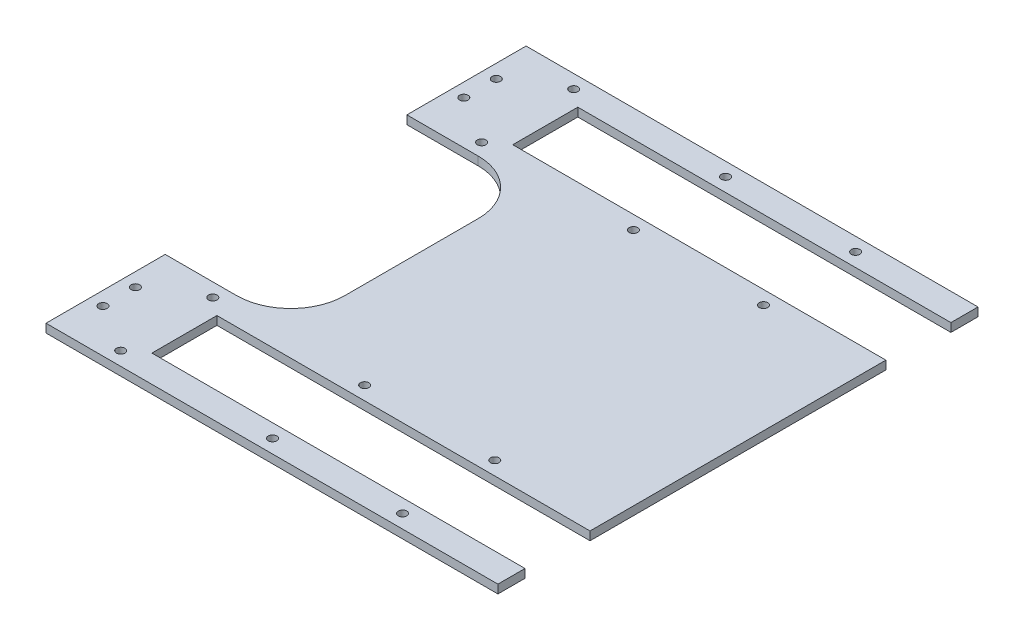
SolidWorks part; units mm, degrees
ref_plane "Front Plane" through (0, 0, 0) normal (0, 0, 1) x (1, 0, 0)
ref_plane "Top Plane" through (0, 0, 0) normal (0, 1, 0) x (1, 0, 0)
ref_plane "Right Plane" through (0, 0, 0) normal (1, 0, 0) x (0, 0, -1)
sketch "Sketch1" plane through (0, 0, 0) normal (0, 1, 0) x (1, 0, 0)
  line L0 (-55.952, 28.5339) -> (-55.9511, 28.5339)
  line L1 (-55.9511, 28.5339) -> (-55.9511, 28.321)
  line L2 (-55.9511, 28.321) -> (-21.4553, 28.321)
  line L3 (-21.4553, 28.321) -> (-21.4553, -28.321)
  line L4 (-21.4553, -28.321) -> (-55.952, -28.321)
  line L5 (-55.952, -28.321) -> (-55.952, -63.881)
  line L6 (-55.952, -63.881) -> (55.046, -63.881)
  line L7 (55.046, -63.881) -> (55.046, -57.531)
  line L8 (55.046, -57.531) -> (32.4585, -57.531)
  line L10 (32.4585, -34.671) -> (55.046, -34.671)
  line L11 (55.046, -34.671) -> (55.046, 34.671)
  line L12 (55.046, 34.671) -> (32.4585, 34.671)
  line L14 (32.4585, 57.531) -> (55.046, 57.531)
  line L15 (55.046, 57.531) -> (55.046, 63.881)
  line L16 (55.046, 63.881) -> (-55.952, 63.881)
  line L17 (-55.952, 63.881) -> (-55.952, 28.5339)
  line L18 (-21.4553, 0) -> (55.046, 0) construction
  line L19 (-55.952, -46.101) -> (-28.5899, -46.101) construction
  line L20 (32.4585, -34.671) -> (-28.5899, -34.671)
  line L21 (-28.5899, -34.671) -> (-28.5899, -46.101)
  line L22 (-28.5899, -46.101) -> (-28.5899, -57.531)
  line L23 (-28.5899, -57.531) -> (32.4585, -57.531)
  line L24 (-28.5899, 57.531) -> (32.4585, 57.531)
  line L25 (-28.5899, 46.101) -> (-28.5899, 57.531)
  line L26 (-28.5899, 34.671) -> (-28.5899, 46.101)
  line L27 (32.4585, 34.671) -> (-28.5899, 34.671)
  dimension "D1" = 28.321
  dimension "D2" = 27.3621
extrude "Boss-Extrude1" add sketch "Sketch1" along normal blind 2
fillet "Fillet1" radius 12.7 2 edges at (-21.4553, 1, 28.321) (-21.4553, 1, -28.321)
sketch "Sketch2" plane through (0, 2, 0) normal (0, 1, 0) x (1, 0, 0)
  line L36 (0, 0) -> (55.046, 0) construction
  line L37 (55.046, -34.671) -> (55.046, 34.671) construction
  circle A0 centre (51.871, 0) radius 1
  circle A1 centre (51.871, 14.1605) radius 1
  circle A2 centre (-18.2803, 0) radius 1
  circle A3 centre (-18.2803, -14.1605) radius 1
  circle A4 centre (-18.2803, 14.1605) radius 1
  circle A5 centre (-36.539, 31.496) radius 1
  circle A6 centre (-0.9481, 31.496) radius 1
  circle A7 centre (29.5319, 31.4883) radius 1
  circle A8 centre (-52.777, 45.1485) radius 1
  circle A9 centre (-52.777, 53.4035) radius 1
  circle A10 centre (-36.539, 60.706) radius 1
  circle A11 centre (-0.9481, 60.706) radius 1
  circle A12 centre (29.5319, 60.7137) radius 1
  circle A13 centre (29.5319, -60.7137) radius 1
  circle A14 centre (-0.9481, -60.706) radius 1
  circle A15 centre (-36.539, -60.706) radius 1
  circle A16 centre (-52.777, -53.4035) radius 1
  circle A17 centre (-52.777, -45.1485) radius 1
  circle A18 centre (29.5319, -31.4883) radius 1
  circle A19 centre (-0.9481, -31.496) radius 1
  circle A20 centre (-36.539, -31.496) radius 1
  circle A21 centre (51.871, -14.1605) radius 1
  dimension "D1" = 2
extrude "Cut-Extrude1" cut sketch "Sketch2" against normal through all both and the other way through all
sketch "Sketch3" plane through (0, 2, 0) normal (0, 1, 0) x (1, 0, 0)
  line L0 (-28.5899, -57.531) -> (-32.3999, -57.531)
  line L1 (-32.3999, -57.531) -> (-32.3999, -34.671)
  line L2 (-32.3999, -34.671) -> (-28.5899, -34.671)
  line L3 (-28.5899, -34.671) -> (-28.5899, -57.531)
  line L4 (-21.4553, 0) -> (55.046, 0) construction
  line L5 (-21.4553, 15.621) -> (-21.4553, -15.621) construction
  line L6 (55.046, -34.671) -> (55.046, 34.671) construction
  line L7 (-28.5899, 34.671) -> (-28.5899, 57.531)
  line L8 (-32.3999, 34.671) -> (-28.5899, 34.671)
  line L9 (-32.3999, 57.531) -> (-32.3999, 34.671)
  line L10 (-28.5899, 57.531) -> (-32.3999, 57.531)
  dimension "D1" = 3.81
extrude "Cut-Extrude2" cut sketch "Sketch3" against normal through all both and the other way through all
sketch "Sketch5" plane through (0, 2, 0) normal (0, 1, 0) x (1, 0, 0)
  line L0 (-18.2803, 0) -> (-8.2803, 0) construction
  line L1 (-8.2803, -34.671) -> (-8.2803, 34.671) construction
  line L2 (55.046, 34.671) -> (-32.3999, 34.671) construction
  line L3 (-8.2803, 34.671) -> (-8.2803, 22.171) construction
  line L4 (-8.2803, -34.671) -> (-8.2803, -22.171) construction
  line L5 (-8.2803, -6.25) -> (-8.2803, 6.25) construction
  line L6 (-8.2803, 22.171) -> (-8.2803, 6.25) construction
  line L7 (-7.2803, 22.171) -> (-7.2803, 6.25)
  line L8 (-9.2803, 22.171) -> (-9.2803, 6.25)
  line L9 (-8.2803, -22.171) -> (-8.2803, -6.25) construction
  line L10 (-7.2803, -22.171) -> (-7.2803, -6.25)
  line L11 (-9.2803, -22.171) -> (-9.2803, -6.25)
  line L12 (-7.2803, 14.2105) -> (-4.2803, 14.2105) construction
  line L13 (-5.7803, 14.2105) -> (-5.7803, 6.25) construction
  line L14 (-3.2803, 22.171) -> (-3.2803, 6.25) construction
  line L15 (-4.2803, 22.171) -> (-4.2803, 6.25)
  line L16 (-2.2803, 22.171) -> (-2.2803, 6.25)
  line L17 (-2.2803, 14.2105) -> (0.7197, 14.2105) construction
  line L18 (-0.7803, 14.2105) -> (-0.7803, 6.25) construction
  line L19 (1.7197, 22.171) -> (1.7197, 6.25) construction
  line L20 (2.7197, 22.171) -> (2.7197, 6.25)
  line L21 (0.7197, 22.171) -> (0.7197, 6.25)
  line L22 (1.7197, -22.171) -> (1.7197, -6.25) construction
  line L23 (2.7197, -22.171) -> (2.7197, -6.25)
  line L24 (0.7197, -22.171) -> (0.7197, -6.25)
  line L25 (-3.2803, -22.171) -> (-3.2803, -6.25) construction
  line L26 (-4.2803, -22.171) -> (-4.2803, -6.25)
  line L27 (-2.2803, -22.171) -> (-2.2803, -6.25)
  arc A0 (-7.2803, 22.171) -> (-9.2803, 22.171) centre (-8.2803, 22.171) ccw
  arc A1 (-9.2803, 6.25) -> (-7.2803, 6.25) centre (-8.2803, 6.25) ccw
  arc A2 (-7.2803, -22.171) -> (-9.2803, -22.171) centre (-8.2803, -22.171) cw
  arc A3 (-9.2803, -6.25) -> (-7.2803, -6.25) centre (-8.2803, -6.25) cw
  arc A4 (-4.2803, 22.171) -> (-2.2803, 22.171) centre (-3.2803, 22.171) cw
  arc A5 (-2.2803, 6.25) -> (-4.2803, 6.25) centre (-3.2803, 6.25) cw
  arc A6 (2.7197, 22.171) -> (0.7197, 22.171) centre (1.7197, 22.171) ccw
  arc A7 (0.7197, 6.25) -> (2.7197, 6.25) centre (1.7197, 6.25) ccw
  arc A8 (2.7197, -22.171) -> (0.7197, -22.171) centre (1.7197, -22.171) cw
  arc A9 (0.7197, -6.25) -> (2.7197, -6.25) centre (1.7197, -6.25) cw
  arc A10 (-4.2803, -22.171) -> (-2.2803, -22.171) centre (-3.2803, -22.171) ccw
  arc A11 (-2.2803, -6.25) -> (-4.2803, -6.25) centre (-3.2803, -6.25) ccw
  point P8 (-8.2803, 0)
  point P13 (-8.2803, 0)
  point P14 (-8.2803, 14.2105)
  point P19 (-8.2803, -14.2105)
  point P30 (-3.2803, 14.2105)
  point P41 (1.7197, 14.2105)
  point P48 (1.7197, -14.2105)
  point P55 (-3.2803, -14.2105)
  dimension "D1" = 10
  dimension "D2" = 3
  dimension "D3" = 12.5
  dimension "D4" = 12.5
  dimension "D5" = 2
  dimension "D6" = 3
extrude "Cut-Extrude3" cut sketch "Sketch5" against normal through all
sketch "Sketch6" plane through (0, 2, 0) normal (0, 1, 0) x (1, 0, 0)
  line L0 (2.7197, 14.2105) -> (8.7197, 14.2105) construction
  line L1 (2.7197, 6.25) -> (2.7197, 22.171) construction
  line L2 (0, 0) -> (8.7197, 0) construction
  line L3 (8.7197, -5) -> (8.7197, 5)
  line L4 (8.7197, 5) -> (11.7197, 5) construction
  line L5 (11.7197, 5) -> (26.6806, 10.4453) construction
  line L6 (-9.2803, 22.171) -> (-9.2803, 6.25) construction
  line L7 (19.2001, 7.7227) -> (26.6806, 10.4453) construction
  line L10 (22.9403, 9.084) -> (11.7197, 5)
  line L11 (22.9403, 9.084) -> (11.7197, 5) construction
  line L12 (23.2824, 8.1443) -> (12.0617, 4.0603)
  line L13 (22.5983, 10.0237) -> (11.3777, 5.9397)
  line L14 (35.4403, 9.084) -> (24.2197, 5) construction
  line L15 (35.7824, 8.1443) -> (24.5617, 4.0603)
  line L16 (35.0983, 10.0237) -> (23.8777, 5.9397)
  line L17 (47.9403, 9.084) -> (36.7197, 5) construction
  line L18 (48.2824, 8.1443) -> (37.0617, 4.0603)
  line L19 (47.5983, 10.0237) -> (36.3777, 5.9397)
  line L20 (22.9403, 9.084) -> (35.4403, 9.084) construction
  line L21 (17.33, 7.042) -> (17.33, 15.542) construction
  line L22 (22.8709, 17.7515) -> (11.6503, 13.6675) construction
  line L23 (23.2129, 16.8118) -> (11.9923, 12.7279)
  line L24 (22.5289, 18.6912) -> (11.3083, 14.6072)
  line L25 (35.3709, 17.7515) -> (24.1503, 13.6675) construction
  line L26 (35.7129, 16.8118) -> (24.4923, 12.7279)
  line L27 (35.0289, 18.6912) -> (23.8083, 14.6072)
  line L28 (47.8709, 17.7515) -> (36.6503, 13.6675) construction
  line L29 (48.2129, 16.8118) -> (36.9923, 12.7279)
  line L30 (47.5289, 18.6912) -> (36.3083, 14.6072)
  line L31 (22.8709, 17.7515) -> (35.3709, 17.7515) construction
  line L32 (8.7197, 0) -> (51.871, 0) construction
  line L33 (47.9403, -9.084) -> (36.7197, -5) construction
  line L34 (48.2824, -8.1443) -> (37.0617, -4.0603)
  line L35 (47.5983, -10.0237) -> (36.3777, -5.9397)
  line L36 (35.4403, -9.084) -> (24.2197, -5) construction
  line L37 (35.7824, -8.1443) -> (24.5617, -4.0603)
  line L38 (35.0983, -10.0237) -> (23.8777, -5.9397)
  line L39 (22.9403, -9.084) -> (11.7197, -5) construction
  line L40 (23.2824, -8.1443) -> (12.0617, -4.0603)
  line L41 (22.5983, -10.0237) -> (11.3777, -5.9397)
  line L42 (47.8709, -17.7515) -> (36.6503, -13.6675) construction
  line L43 (48.2129, -16.8118) -> (36.9923, -12.7279)
  line L44 (47.5289, -18.6912) -> (36.3083, -14.6072)
  line L45 (35.3709, -17.7515) -> (24.1503, -13.6675) construction
  line L46 (35.7129, -16.8118) -> (24.4923, -12.7279)
  line L47 (35.0289, -18.6912) -> (23.8083, -14.6072)
  line L48 (22.8709, -17.7515) -> (11.6503, -13.6675) construction
  line L49 (23.2129, -16.8118) -> (11.9923, -12.7279)
  line L50 (22.5289, -18.6912) -> (11.3083, -14.6072)
  arc A0 (23.2824, 8.1443) -> (22.5983, 10.0237) centre (22.9403, 9.084) ccw
  arc A1 (11.3777, 5.9397) -> (12.0617, 4.0603) centre (11.7197, 5) ccw
  arc A2 (35.7824, 8.1443) -> (35.0983, 10.0237) centre (35.4403, 9.084) ccw
  arc A3 (23.8777, 5.9397) -> (24.5617, 4.0603) centre (24.2197, 5) ccw
  arc A4 (48.2824, 8.1443) -> (47.5983, 10.0237) centre (47.9403, 9.084) ccw
  arc A5 (36.3777, 5.9397) -> (37.0617, 4.0603) centre (36.7197, 5) ccw
  arc A6 (23.2129, 16.8118) -> (22.5289, 18.6912) centre (22.8709, 17.7515) ccw
  arc A7 (11.3083, 14.6072) -> (11.9923, 12.7279) centre (11.6503, 13.6675) ccw
  arc A8 (35.7129, 16.8118) -> (35.0289, 18.6912) centre (35.3709, 17.7515) ccw
  arc A9 (23.8083, 14.6072) -> (24.4923, 12.7279) centre (24.1503, 13.6675) ccw
  arc A10 (48.2129, 16.8118) -> (47.5289, 18.6912) centre (47.8709, 17.7515) ccw
  arc A11 (36.3083, 14.6072) -> (36.9923, 12.7279) centre (36.6503, 13.6675) ccw
  arc A12 (48.2824, -8.1443) -> (47.5983, -10.0237) centre (47.9403, -9.084) cw
  arc A13 (36.3777, -5.9397) -> (37.0617, -4.0603) centre (36.7197, -5) cw
  arc A14 (35.7824, -8.1443) -> (35.0983, -10.0237) centre (35.4403, -9.084) cw
  arc A15 (23.8777, -5.9397) -> (24.5617, -4.0603) centre (24.2197, -5) cw
  arc A16 (23.2824, -8.1443) -> (22.5983, -10.0237) centre (22.9403, -9.084) cw
  arc A17 (11.3777, -5.9397) -> (12.0617, -4.0603) centre (11.7197, -5) cw
  arc A18 (48.2129, -16.8118) -> (47.5289, -18.6912) centre (47.8709, -17.7515) cw
  arc A19 (36.3083, -14.6072) -> (36.9923, -12.7279) centre (36.6503, -13.6675) cw
  arc A20 (35.7129, -16.8118) -> (35.0289, -18.6912) centre (35.3709, -17.7515) cw
  arc A21 (23.8083, -14.6072) -> (24.4923, -12.7279) centre (24.1503, -13.6675) cw
  arc A22 (23.2129, -16.8118) -> (22.5289, -18.6912) centre (22.8709, -17.7515) cw
  arc A23 (11.3083, -14.6072) -> (11.9923, -12.7279) centre (11.6503, -13.6675) cw
  point P9 (8.7197, 0)
  point P18 (17.33, 7.042)
  point P26 (29.83, 7.042)
  point P33 (42.33, 7.042)
  point P44 (29.7606, 15.7095)
  point P47 (17.2606, 15.7095)
  point P59 (42.2606, 15.7095)
  point P68 (42.33, -7.042)
  point P75 (29.83, -7.042)
  point P82 (17.33, -7.042)
  point P89 (42.2606, -15.7095)
  point P96 (29.7606, -15.7095)
  point P103 (17.2606, -15.7095)
  dimension "D6" = 160
  dimension "D1" = 6
  dimension "D2" = 10
  dimension "D3" = 3
  dimension "D4" = 2
  dimension "D5" = 8.7197
  dimension "D7" = 3
  dimension "D8" = 12.5
  dimension "D9" = 8.5
  dimension "D10" = 3
  dimension "D11" = 12.5
  dimension "D12" = 11.9407
  dimension "D13" = 13.6675
  dimension "D14" = 11.6503
extrude "Cut-Extrude4" cut sketch "Sketch6" against normal through all contours L23 A7 L24 A6 | L26 A9 L27 A8 | L29 A11 L30 A10 | L18 A5 L19 A4 | L15 A3 L16 A2 | L12 A1 L13 A0 | L38 A15 L37 A14 | L41 A17 L40 A16 | L35 A13 L34 A12 | L43 A19 L44 A18 | L46 A21 L47 A20 | L49 A23 L50 A22
sketch "Sketch7" plane through (0, 0, 0) normal (0, -1, 0) x (1, 0, 0)
  line L0 (-57.9178, 63.881) -> (-55.952, 63.881)
  line L1 (-55.952, 63.881) -> (-55.952, 28.321)
  line L2 (-55.952, 28.321) -> (-57.9178, 28.321)
  line L3 (-57.9178, 28.321) -> (-57.9178, 63.881)
  line L4 (-21.4553, 0) -> (55.046, 0) construction
  line L5 (-21.4553, -15.621) -> (-21.4553, 15.621) construction
  line L6 (55.046, 34.671) -> (55.046, -34.671) construction
  line L7 (-57.9178, -28.321) -> (-57.9178, -63.881)
  line L8 (-55.952, -28.321) -> (-57.9178, -28.321)
  line L9 (-55.952, -63.881) -> (-55.952, -28.321)
  line L10 (-57.9178, -63.881) -> (-55.952, -63.881)
  circle A0 centre (-54.7428, 53.4035) radius 1
  circle A1 centre (-54.7428, 45.1485) radius 1
  circle A2 centre (-54.7428, -45.1485) radius 1
  circle A3 centre (-54.7428, -53.4035) radius 1
extrude "Cut-Extrude5" cut sketch "Sketch7" against normal through all
sketch "Sketch9" plane through (0, 0, 0) normal (0, -1, 0) x (1, 0, 0)
  line L0 (-52.777, 53.4035) -> (-47.697, 53.4035) construction
  line L1 (-52.777, 45.1485) -> (-47.697, 45.1485) construction
  line L2 (-55.952, 63.881) -> (-50.872, 63.881)
  line L3 (-55.952, 63.881) -> (55.046, 63.881) construction
  line L4 (-50.872, 63.881) -> (-50.872, 28.321)
  line L5 (-34.1553, 28.321) -> (-55.952, 28.321) construction
  line L6 (-50.872, 28.321) -> (-55.952, 28.321)
  line L7 (-55.952, 28.321) -> (-55.952, 63.881)
  line L8 (-21.4553, 0) -> (55.046, 0) construction
  line L9 (-21.4553, -15.621) -> (-21.4553, 15.621) construction
  line L10 (55.046, 34.671) -> (55.046, -34.671) construction
  line L11 (-52.777, -45.1485) -> (-47.697, -45.1485) construction
  line L12 (-52.777, -53.4035) -> (-47.697, -53.4035) construction
  line L13 (-55.952, -28.321) -> (-55.952, -63.881)
  line L14 (-50.872, -28.321) -> (-55.952, -28.321)
  line L15 (-50.872, -63.881) -> (-50.872, -28.321)
  line L16 (-55.952, -63.881) -> (-50.872, -63.881)
  circle A0 centre (-47.697, 53.4035) radius 1
  circle A1 centre (-47.697, 45.1485) radius 1
  arc A2 (-53.7599, 53.2194) -> (-53.7599, 53.5876) centre (-52.777, 53.4035) ccw construction
  circle A3 centre (-47.697, -45.1485) radius 1
  circle A4 centre (-47.697, -53.4035) radius 1
  dimension "D1" = 5.08
  dimension "D2" = 5.08
  dimension "D3" = 5.08
extrude "Cut-Extrude6" cut sketch "Sketch9" against normal through all
sketch "Sketch10" plane through (0, 2, 0) normal (0, 1, 0) x (1, 0, 0)
  line L1 (-16.6494, -19.9028) -> (-19.9112, -19.9028)
  line L2 (-16.6494, -19.9028) -> (-16.6494, 19.9028)
  line L3 (-16.6494, 19.9028) -> (-19.9112, 19.9028)
  line L4 (-19.9112, -19.9028) -> (-19.9112, 19.9028)
  line L5 (-16.6494, -19.9028) -> (-19.9112, 19.9028) construction
  line L6 (-16.6494, 19.9028) -> (-19.9112, -19.9028) construction
  line L7 (53.619, -18.7932) -> (50.123, -18.7932)
  line L8 (53.619, -18.7932) -> (53.619, 18.7932)
  line L9 (53.619, 18.7932) -> (50.123, 18.7932)
  line L10 (50.123, -18.7932) -> (50.123, 18.7932)
  line L11 (53.619, -18.7932) -> (50.123, 18.7932) construction
  line L12 (53.619, 18.7932) -> (50.123, -18.7932) construction
  point P0 (-18.2803, 0)
  point P6 (51.871, 0)
extrude "Boss-Extrude2" add sketch "Sketch10" against normal up to surface (2 mm away) up to face at (-47.697, 0, 44.1485)
sketch "Sketch11" plane through (0, 2, 0) normal (0, 1, 0) x (1, 0, 0)
  line L0 (-32.3999, -34.671) -> (-32.3999, -42.291) construction
  line L1 (-32.3999, -34.671) -> (-32.3999, -57.531) construction
  line L2 (-32.3999, -42.291) -> (-50.872, -42.291)
  line L3 (-50.872, -28.321) -> (-50.872, -63.881) construction
  line L4 (-50.872, -42.291) -> (-50.872, -34.671)
  line L5 (-50.872, -34.671) -> (-32.3999, -34.671)
  line L6 (-32.3999, -34.671) -> (-32.3999, -42.291)
  dimension "D1" = 7.62
extrude "Cut-Extrude7" cut sketch "Sketch11" against normal through all
sketch "Sketch12" plane through (0, 2, 0) normal (0, 1, 0) x (1, 0, 0)
  line L0 (-32.3999, 34.671) -> (-69.841, 34.671)
  line L1 (-69.841, 34.671) -> (-69.841, 70.714)
  line L2 (-69.841, 70.714) -> (61.6729, 70.714)
  line L3 (61.6729, 70.714) -> (61.6729, 34.671)
  line L4 (61.6729, 34.671) -> (-32.3999, 34.671)
  dimension "D1" = 36.043
  dimension "D2" = 131.5138
  dimension "D3" = 69.841
extrude "Cut-Extrude8" cut sketch "Sketch12" against normal through all
sketch "Sketch13" plane through (0, 2, 0) normal (0, 1, 0) x (1, 0, 0)
  line L3 (55.046, 49.911) -> (-32.3999, 49.911)
  line L4 (55.046, 56.261) -> (55.046, 49.911)
  line L5 (-50.872, 56.261) -> (55.046, 56.261)
  line L18 (-32.3999, 34.671) -> (-50.872, 34.671)
  line L19 (-50.872, 56.261) -> (-50.872, 34.671)
  line L20 (-32.3999, 34.671) -> (-32.3999, 49.911)
  circle A0 centre (29.5319, 53.0937) radius 1
  circle A16 centre (-0.9481, 53.086) radius 1
  circle A17 centre (-36.539, 53.086) radius 1
  circle A18 centre (-47.697, 45.7835) radius 1
  circle A19 centre (-47.697, 37.5285) radius 1
extrude "Boss-Extrude3" add sketch "Sketch13" against normal up to surface (2 mm away) up to face at (42.2606, 0, 15.7095)
sketch "Sketch14" plane through (0, 2, 0) normal (0, 1, 0) x (1, 0, 0)
  line L6 (-32.3999, -42.291) -> (-50.872, -42.291)
  line L7 (-50.872, -42.291) -> (-50.872, -63.881)
  line L8 (-50.872, -63.881) -> (55.046, -63.881)
  line L9 (55.046, -63.881) -> (55.046, -57.531)
  line L10 (55.046, -57.531) -> (-32.3999, -57.531)
  line L11 (-32.3999, -57.531) -> (-32.3999, -42.291)
  line L12 (-32.3999, -42.291) -> (-50.872, -42.291)
  line L13 (-50.872, -42.291) -> (-50.872, -63.881)
  line L14 (-50.872, -63.881) -> (55.046, -63.881)
  line L15 (55.046, -63.881) -> (55.046, -57.531)
  line L16 (55.046, -57.531) -> (-32.3999, -57.531)
  line L17 (-32.3999, -57.531) -> (-32.3999, -42.291)
  dimension "D1" = 0
extrude "Cut-Extrude9" cut sketch "Sketch14" against normal through all
sketch "Sketch15" plane through (0, 2, 0) normal (0, 1, 0) x (1, 0, 0)
  line L0 (-21.4553, 0) -> (55.046, 0) construction
  line L1 (-21.4553, 15.621) -> (-21.4553, -15.621) construction
  line L2 (55.046, -34.671) -> (55.046, 34.671) construction
  line L3 (55.046, 56.261) -> (-50.872, 56.261) construction
  line L4 (55.046, 49.911) -> (55.046, 56.261) construction
  line L5 (-32.3999, 34.671) -> (-32.3999, 49.911) construction
  line L6 (-32.3999, 49.911) -> (55.046, 49.911) construction
  line L7 (55.046, 56.261) -> (-50.872, 56.261) construction
  line L8 (55.046, 49.911) -> (55.046, 56.261) construction
  line L9 (-32.3999, 34.671) -> (-32.3999, 49.911) construction
  line L10 (-32.3999, 49.911) -> (55.046, 49.911) construction
  line L11 (-32.3999, 34.671) -> (-50.872, 34.671) construction
  line L12 (-50.872, 56.261) -> (-50.872, 28.321) construction
  line L13 (-50.872, 34.671) -> (-50.872, 56.261) construction
  line L14 (-50.872, -34.671) -> (-50.872, -56.261)
  line L15 (-32.3999, -34.671) -> (-50.872, -34.671)
  line L16 (-32.3999, -49.911) -> (55.046, -49.911)
  line L17 (-32.3999, -34.671) -> (-32.3999, -49.911)
  line L18 (55.046, -49.911) -> (55.046, -56.261)
  line L19 (55.046, -56.261) -> (-50.872, -56.261)
  circle A0 centre (29.5319, 53.0937) radius 1 construction
  circle A1 centre (-0.9481, 53.086) radius 1 construction
  circle A2 centre (-36.539, 53.086) radius 1 construction
  circle A3 centre (-47.697, 37.5285) radius 1 construction
  circle A4 centre (-47.697, 45.7835) radius 1 construction
  circle A5 centre (29.5319, 53.0937) radius 1 construction
  circle A6 centre (-0.9481, 53.086) radius 1 construction
  circle A7 centre (-36.539, 53.086) radius 1 construction
  circle A8 centre (-47.697, 37.5285) radius 1 construction
  circle A9 centre (-47.697, 45.7835) radius 1 construction
  circle A10 centre (-47.697, -45.7835) radius 1
  circle A11 centre (-47.697, -37.5285) radius 1
  circle A12 centre (-36.539, -53.086) radius 1
  circle A13 centre (-0.9481, -53.086) radius 1
  circle A14 centre (29.5319, -53.0937) radius 1
extrude "Boss-Extrude6" add sketch "Sketch15" against normal up to surface (2 mm away) up to face at (42.2606, 0, 15.7095)
sketch "Sketch16" plane through (0, 0, 0) normal (0, -1, 0) x (1, 0, 0)
  line L1 (-50.3879, -51.1853) -> (-45.8759, -51.1853)
  line L2 (-50.3879, -51.1853) -> (-50.3879, -33.0367)
  line L3 (-50.3879, -33.0367) -> (-45.8759, -33.0367)
  line L4 (-45.8759, -51.1853) -> (-45.8759, -33.0367)
  line L5 (-50.3879, -51.1853) -> (-45.8759, -33.0367) construction
  line L6 (-50.3879, -33.0367) -> (-45.8759, -51.1853) construction
  line L7 (-50.2413, 35.4433) -> (-43.9893, 35.4433)
  line L8 (-50.2413, 35.4433) -> (-50.2413, 48.5156)
  line L9 (-50.2413, 48.5156) -> (-43.9893, 48.5156)
  line L10 (-43.9893, 35.4433) -> (-43.9893, 48.5156)
  line L11 (-50.2413, 35.4433) -> (-43.9893, 48.5156) construction
  line L12 (-50.2413, 48.5156) -> (-43.9893, 35.4433) construction
  point P0 (-48.1319, -42.111)
  point P5 (-47.1153, 41.9794)
extrude "Boss-Extrude7" add sketch "Sketch16" against normal up to surface (2 mm away) up to face at (-6.0429, 2, 0)
sketch "Sketch17" plane through (0, 2, 0) normal (0, 1, 0) x (1, 0, 0)
  line L0 (-50.872, -38.481) -> (-47.697, -38.481) construction
  line L1 (-32.3999, -42.291) -> (-50.872, -42.291) construction
  line L2 (-21.4553, 0) -> (55.046, 0) construction
  line L3 (-21.4553, 15.621) -> (-21.4553, -15.621) construction
  line L4 (-50.872, -28.321) -> (-50.872, -56.261) construction
  line L5 (-32.3999, -34.671) -> (-32.3999, -49.911) construction
  line L6 (-32.3999, -42.291) -> (-32.3999, -34.671) construction
  line L7 (-32.3999, -38.481) -> (-54.8352, -38.481) construction
  line L8 (55.046, -34.671) -> (55.046, 34.671) construction
  circle A0 centre (-47.697, -38.481) radius 1
  circle A1 centre (-36.539, -31.496) radius 1 construction
  circle A2 centre (-47.697, -46.101) radius 1
  circle A3 centre (-47.697, 38.481) radius 1
  circle A4 centre (-47.697, 46.101) radius 1
  dimension "D2" = 3.175
extrude "Cut-Extrude10" cut sketch "Sketch17" against normal through all
sketch "Sketch18" plane through (0, 0, 0) normal (0, -1, 0) x (1, 0, 0)
  line L1 (51.2141, -25.5889) -> (-19.9355, -25.5889)
  line L2 (51.2141, -25.5889) -> (51.2141, 25.5889)
  line L3 (51.2141, 25.5889) -> (-19.9355, 25.5889)
  line L4 (-19.9355, -25.5889) -> (-19.9355, 25.5889)
  line L5 (51.2141, -25.5889) -> (-19.9355, 25.5889) construction
  line L6 (51.2141, 25.5889) -> (-19.9355, -25.5889) construction
  point P0 (15.6393, 0)
extrude "Boss-Extrude8" add sketch "Sketch18" against normal up to surface (2 mm away) up to face at (-47.697, 2, -45.101)
